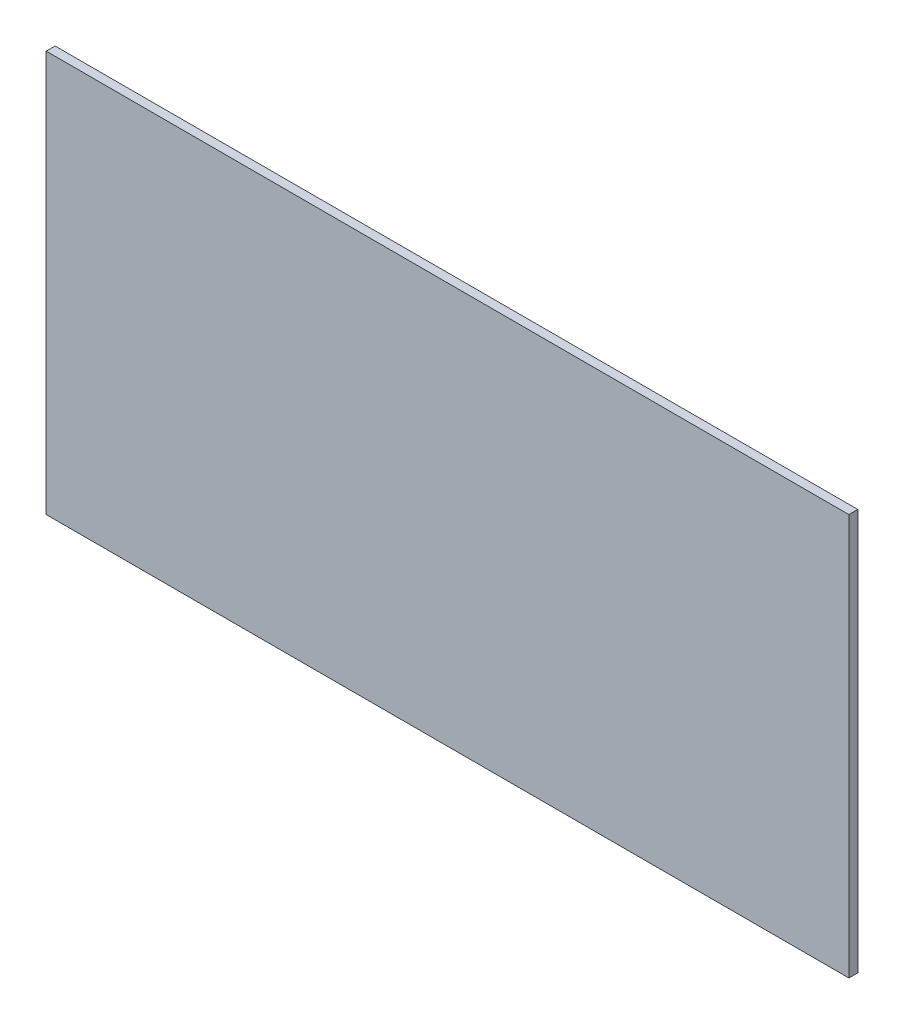
SolidWorks part; units mm, degrees
ref_plane "Front Plane" through (0, 0, 0) normal (0, 0, 1) x (1, 0, 0)
ref_plane "Top Plane" through (0, 0, 0) normal (0, 1, 0) x (1, 0, 0)
ref_plane "Right Plane" through (0, 0, 0) normal (1, 0, 0) x (0, 0, -1)
sketch "Sketch1" plane through (0, 0, 0) normal (0, 0, 1) x (1, 0, 0)
  line L1 (-90, 45) -> (90, 45)
  line L2 (-90, 45) -> (-90, -45)
  line L3 (-90, -45) -> (90, -45)
  line L4 (90, 45) -> (90, -45)
  line L5 (-90, 45) -> (90, -45) construction
  line L6 (-90, -45) -> (90, 45) construction
  point P0 (0, 0)
  dimension "D1" = 180
  dimension "D2" = 90
extrude "Boss-Extrude1" add sketch "Sketch1" along normal mid plane 2
